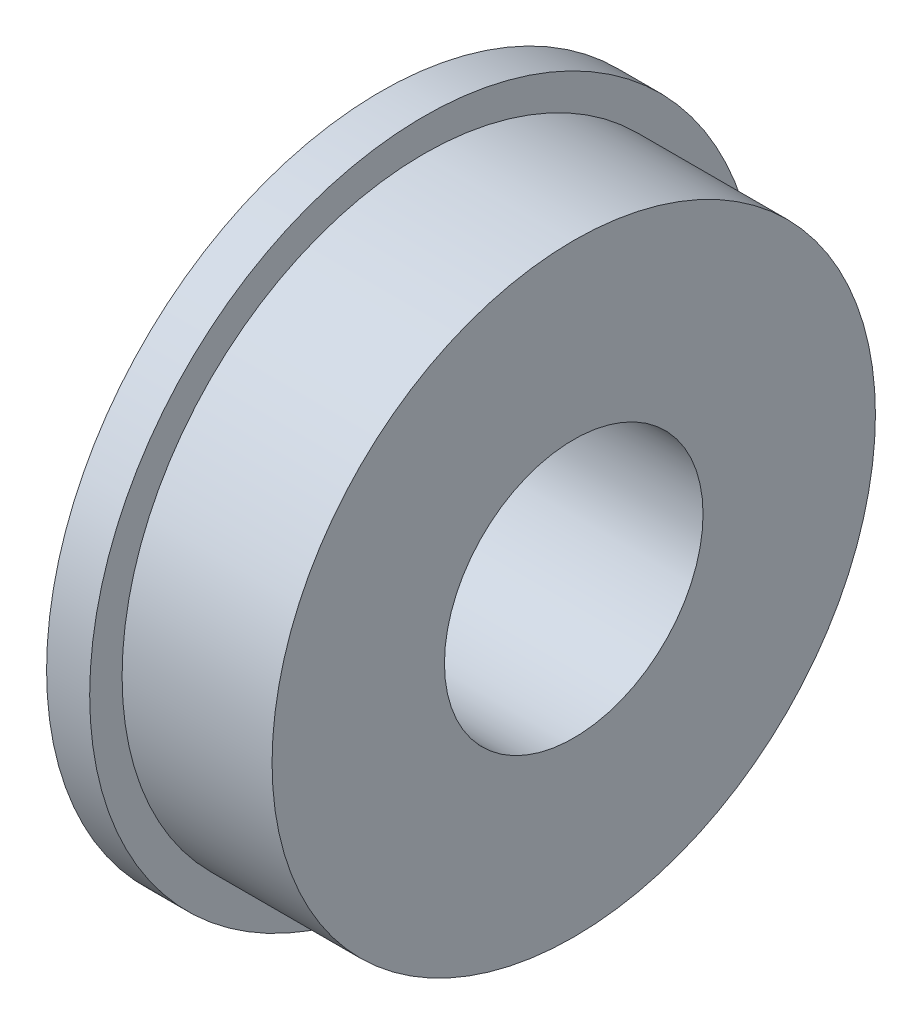
SolidWorks part; units mm, degrees
ref_plane "Front Plane" through (0, 0, 0) normal (0, 0, 1) x (1, 0, 0)
ref_plane "Top Plane" through (0, 0, 0) normal (0, 1, 0) x (1, 0, 0)
ref_plane "Right Plane" through (0, 0, 0) normal (1, 0, 0) x (0, 0, -1)
ref_plane "Plane1" through (0, 0, 0) normal (0, 0, -1) x (-1, 0, 0)
sketch "Sketch1" plane through (0, 0, 0) normal (0, 0, -1) x (-1, 0, 0)
  line L0 (0, 6.35) -> (-0.381, 6.35)
  line L1 (-0.381, 6.35) -> (-0.381, 9.906)
  line L2 (-0.381, 9.906) -> (0, 9.906)
  line L3 (0, 9.906) -> (0, 12.3063)
  line L4 (0, 12.3063) -> (-1.5875, 12.3063)
  line L5 (-1.5875, 12.3063) -> (-1.5875, 11.1125)
  line L6 (-1.5875, 11.1125) -> (-7.112, 11.1125)
  line L7 (-7.112, 11.1125) -> (-7.112, 4.7625)
  line L8 (-7.112, 4.7625) -> (0, 4.7625)
  line L9 (0, 4.7625) -> (0, 6.35)
  line L10 (-7.112, 0) -> (0, 0) construction
revolve "Revolve1" add sketch "Sketch1" angle 360 about L10
